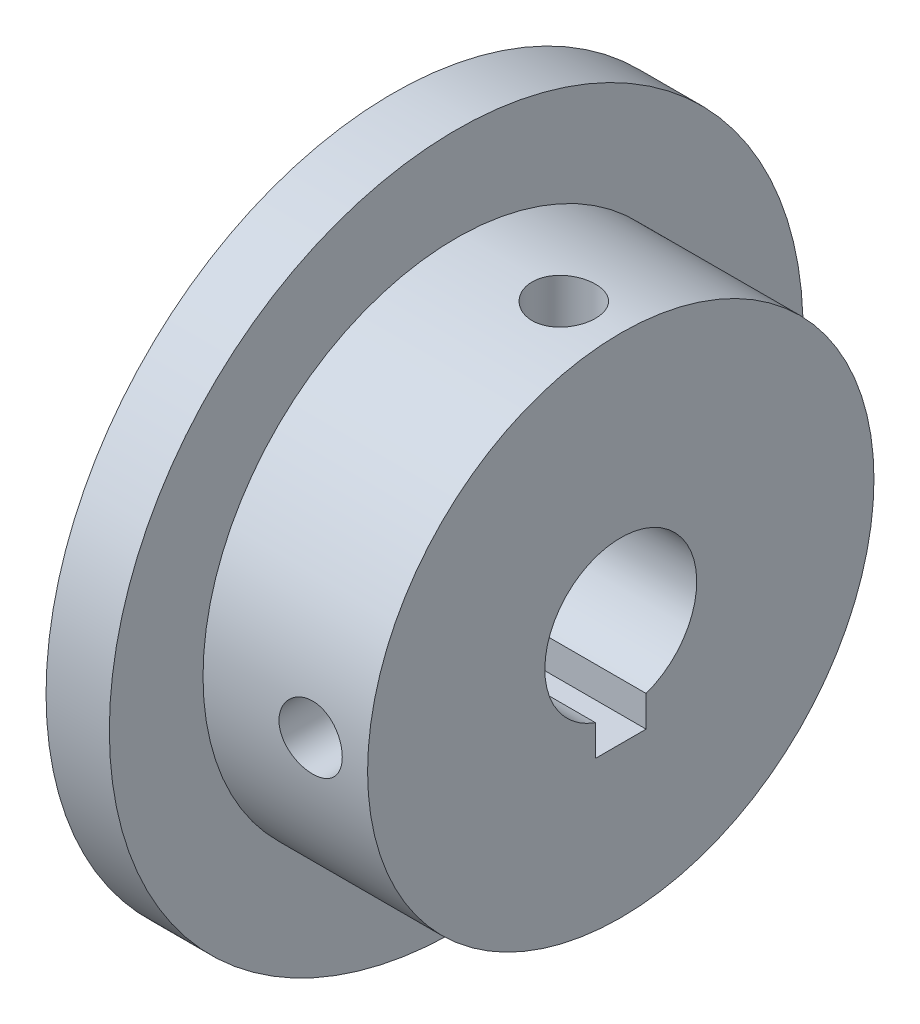
SolidWorks part; units mm, degrees
material "合金钢 (SS)"
ref_plane "前视基准面" through (0, 0, 0) normal (0, 0, 1) x (1, 0, 0)
ref_plane "上视基准面" through (0, 0, 0) normal (0, 1, 0) x (1, 0, 0)
ref_plane "右视基准面" through (0, 0, 0) normal (1, 0, 0) x (0, 0, -1)
other "10齿"
sketch "草图1" plane through (0, 0, 0) normal (0, 0, 1) x (1, 0, 0)
  line L0 (0, 0) -> (22, 0) construction
  line L1 (0, 0) -> (0, 27.4)
  line L2 (0, 27.4) -> (5, 27.4)
  line L3 (5, 27.4) -> (5, 20)
  line L4 (5, 20) -> (22, 20)
  line L5 (22, 20) -> (22, 0)
  line L6 (0, 0) -> (22, 0)
  dimension "D1" = 54.8
  dimension "D2" = 5
  dimension "D3" = 22
  dimension "D4" = 20
revolve "旋转1" add sketch "草图1" angle 360 about L0
sketch "草图2" plane through (0, 0, 0) normal (-1, 0, 0) x (0, 0, 1)
  circle A0 centre (0, 0) radius 6
  dimension "D1" = 12
extrude "切除-拉伸1" cut sketch "草图2" against normal through all
hole_wizard "M6 螺纹孔1" positions "3D草图1" profile "草图3" tap size "M6" standard "GB"
sketch3d "3D草图1"
  line L0 (22, 0, 20) -> (5, 0, 20) construction
  circle A0 centre (22, 0, 0) radius 20 construction
  circle A1 centre (5, 0, 0) radius 20 construction
  point P22 (13.5, 0, 20)
  point P29 (2, 0, 0)
  point P32 (-15, 0, 0)
sketch "草图3" plane through (13.5, 0, 20) normal (1, 0, 0) x (0, -1, 0)
  line L0 (0, 0) -> (0, 40)
  line L1 (0, 40) -> (2.5, 40)
  line L2 (2.5, 40) -> (2.5, 0)
  line L5 (2.5, 0) -> (0, 0)
  line L11 (0, -6.35) -> (0, 107.95) construction
  dimension "通孔螺纹孔钻头直径" = 5
  dimension "通孔螺纹孔钻头深度" = 40
cosmetic thread "孔螺蚊线1" parameters "D2"=6
pattern_circular "阵列(圆周)1" count 2 every 90 about axis through (22, 0, 0) along (-1, 0, 0) of "M6 螺纹孔1"
sketch "草图4" plane through (0, 0, 0) normal (-1, 0, 0) x (0, 0, 1)
  line L1 (-2, -8.1) -> (2, -8.1)
  line L2 (-2, -8.1) -> (-2, -3.9)
  line L3 (-2, -3.9) -> (2, -3.9)
  line L4 (2, -8.1) -> (2, -3.9)
  line L5 (-2, -8.1) -> (2, -3.9) construction
  line L6 (-2, -3.9) -> (2, -8.1) construction
  circle A0 centre (0, 0) radius 6 construction
  point P0 (0, -6)
  dimension "D1" = 4.2
  dimension "D2" = 4
extrude "切除-拉伸2" cut sketch "草图4" against normal up to next
sketch "草图5" plane through (22, 0, 0) normal (1, 0, 0) x (0, 0, -1)
  circle A0 centre (0, 0) radius 20 construction
  circle A1 centre (0, 0) radius 20
extrude "切除-拉伸3" cut sketch "草图5" against normal blind 4
